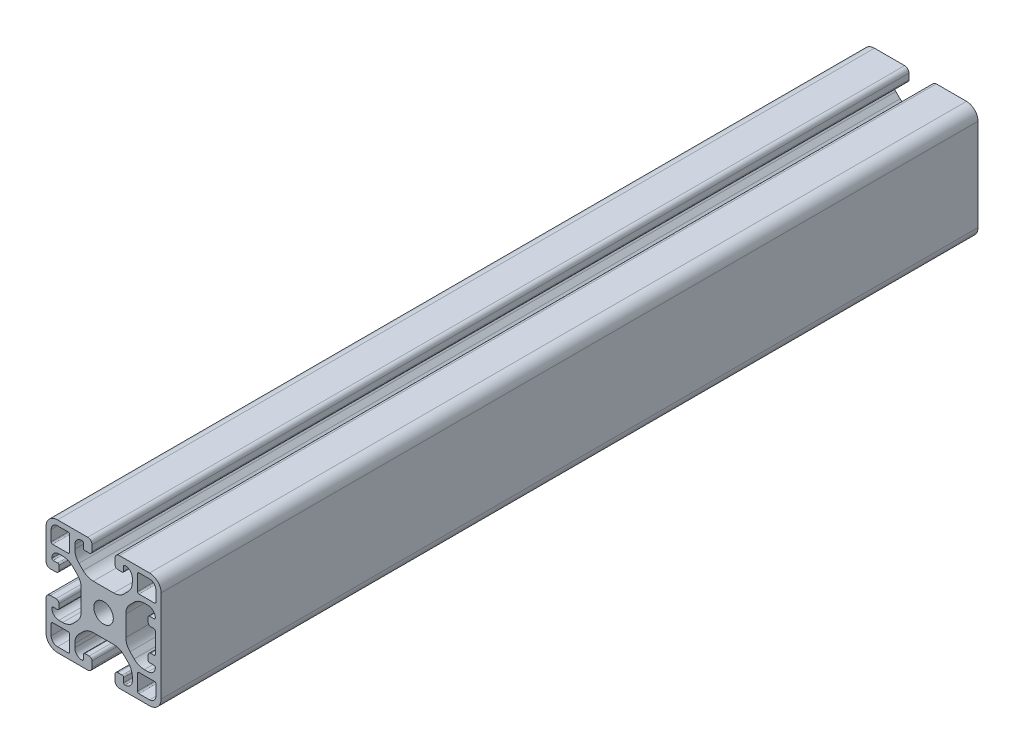
SolidWorks part; units mm, degrees
ref_plane "Piano frontale" through (0, 0, 0) normal (0, 0, 1) x (1, 0, 0)
ref_plane "Piano superiore" through (0, 0, 0) normal (0, 1, 0) x (1, 0, 0)
ref_plane "Piano destro" through (0, 0, 0) normal (1, 0, 0) x (0, 0, -1)
ref_plane "Piano1" through (0, 0, -340) normal (0, 0, -1) x (-1, 0, 0)
sketch "Schizzo1" plane through (0, 0, -340) normal (0, 0, -1) x (-1, 0, 0)
  line L0 (-12.3, -18.2) -> (-16, -18.2)
  line L1 (-18.2, -16) -> (-18.2, -12.3)
  line L2 (-17.7, -11.8) -> (-12.3, -11.8)
  line L3 (-11.8, -12.3) -> (-11.8, -17.7)
  line L4 (-11.8, 17.7) -> (-11.8, 12.3)
  line L5 (-12.3, 11.8) -> (-17.7, 11.8)
  line L6 (-18.2, 12.3) -> (-18.2, 16)
  line L7 (-16, 18.2) -> (-12.3, 18.2)
  line L8 (18.2, 16) -> (18.2, 12.3)
  line L9 (17.7, 11.8) -> (12.3, 11.8)
  line L10 (11.8, 12.3) -> (11.8, 17.7)
  line L11 (12.3, 18.2) -> (16, 18.2)
  line L12 (6.5, -15.5) -> (5, -15.5)
  line L13 (4, -16.5) -> (4, -18.5)
  line L14 (5.5, -20) -> (16, -20)
  line L15 (20, -16) -> (20, -5.5)
  line L16 (18.5, -4) -> (16.5, -4)
  line L17 (15.5, -5) -> (15.5, -6.5)
  line L18 (16, -7) -> (17.55, -7)
  line L19 (18, -7.45) -> (18, -7.5)
  line L20 (15.5, -10) -> (14.1924, -10)
  line L21 (10.6569, -8.5355) -> (9.2145, -7.0931)
  line L22 (7.75, -3.5576) -> (7.75, 3.5576)
  line L23 (9.2145, 7.0931) -> (10.6569, 8.5355)
  line L24 (14.1924, 10) -> (15.5, 10)
  line L25 (18, 7.5) -> (18, 7.45)
  line L26 (17.55, 7) -> (16, 7)
  line L27 (15.5, 6.5) -> (15.5, 5)
  line L28 (16.5, 4) -> (18.5, 4)
  line L29 (20, 5.5) -> (20, 16)
  line L30 (16, 20) -> (5.5, 20)
  line L31 (4, 18.5) -> (4, 16.5)
  line L32 (5, 15.5) -> (6.5, 15.5)
  line L33 (7, 16) -> (7, 17.55)
  line L34 (7.45, 18) -> (7.5, 18)
  line L35 (10, 15.5) -> (10, 14.1924)
  line L36 (8.5355, 10.6569) -> (7.0931, 9.2145)
  line L37 (3.5576, 7.75) -> (-3.5576, 7.75)
  line L38 (-7.0931, 9.2145) -> (-8.5355, 10.6569)
  line L39 (-10, 14.1924) -> (-10, 15.5)
  line L40 (-7.5, 18) -> (-7.45, 18)
  line L41 (-7, 17.55) -> (-7, 16)
  line L42 (-6.5, 15.5) -> (-5, 15.5)
  line L43 (-4, 16.5) -> (-4, 18.5)
  line L44 (-5.5, 20) -> (-16, 20)
  line L45 (-20, 16) -> (-20, -16)
  line L46 (-16, -20) -> (-5.5, -20)
  line L47 (-4, -18.5) -> (-4, -16.5)
  line L48 (-5, -15.5) -> (-6.5, -15.5)
  line L49 (-7, -16) -> (-7, -17.55)
  line L50 (-7.45, -18) -> (-7.5, -18)
  line L51 (-10, -15.5) -> (-10, -14.1924)
  line L52 (-8.5355, -10.6569) -> (-7.0931, -9.2145)
  line L53 (-3.5576, -7.75) -> (3.5576, -7.75)
  line L54 (7.0931, -9.2145) -> (8.5355, -10.6569)
  line L55 (10, -14.1924) -> (10, -15.5)
  line L56 (7.5, -18) -> (7.45, -18)
  line L57 (7, -17.55) -> (7, -16)
  line L58 (18.2, -12.3) -> (18.2, -16)
  line L59 (16, -18.2) -> (12.3, -18.2)
  line L60 (11.8, -17.7) -> (11.8, -12.3)
  line L61 (12.3, -11.8) -> (17.7, -11.8)
  line L62 (-16, 7) -> (-17.5, 7)
  line L63 (-15.5, 10) -> (-14.1924, 10)
  line L64 (-10.6569, 8.5355) -> (-9.2145, 7.0931)
  line L65 (-7.75, 3.5576) -> (-7.75, -3.5576)
  line L66 (-9.2145, -7.0931) -> (-10.6569, -8.5355)
  line L67 (-14.1924, -10) -> (-15.5, -10)
  line L68 (-17.5, -7) -> (-16, -7)
  line L69 (-15.5, -6.5) -> (-15.5, -5)
  line L70 (-16.5, -4) -> (-17.5, -4)
  line L71 (-18, -3.5) -> (-18, 3.5)
  line L72 (-17.5, 4) -> (-16.5, 4)
  line L73 (-15.5, 5) -> (-15.5, 6.5)
  arc A0 (-16, -18.2) -> (-18.2, -16) centre (-16, -16) cw
  arc A1 (-18.2, -12.3) -> (-17.7, -11.8) centre (-17.7, -12.3) cw
  arc A2 (-12.3, -11.8) -> (-11.8, -12.3) centre (-12.3, -12.3) cw
  arc A3 (-11.8, -17.7) -> (-12.3, -18.2) centre (-12.3, -17.7) cw
  arc A4 (-12.3, 18.2) -> (-11.8, 17.7) centre (-12.3, 17.7) cw
  arc A5 (-11.8, 12.3) -> (-12.3, 11.8) centre (-12.3, 12.3) cw
  arc A6 (-17.7, 11.8) -> (-18.2, 12.3) centre (-17.7, 12.3) cw
  arc A7 (-18.2, 16) -> (-16, 18.2) centre (-16, 16) cw
  arc A8 (16, 18.2) -> (18.2, 16) centre (16, 16) cw
  arc A9 (18.2, 12.3) -> (17.7, 11.8) centre (17.7, 12.3) cw
  arc A10 (12.3, 11.8) -> (11.8, 12.3) centre (12.3, 12.3) cw
  arc A11 (11.8, 17.7) -> (12.3, 18.2) centre (12.3, 17.7) cw
  arc A12 (5, -15.5) -> (4, -16.5) centre (5, -16.5) ccw
  arc A13 (4, -18.5) -> (5.5, -20) centre (5.5, -18.5) ccw
  arc A14 (16, -20) -> (20, -16) centre (16, -16) ccw
  arc A15 (20, -5.5) -> (18.5, -4) centre (18.5, -5.5) ccw
  arc A16 (16.5, -4) -> (15.5, -5) centre (16.5, -5) ccw
  arc A17 (15.5, -6.5) -> (16, -7) centre (16, -6.5) ccw
  arc A18 (17.55, -7) -> (18, -7.45) centre (17.55, -7.45) cw
  arc A19 (18, -7.5) -> (15.5, -10) centre (15.5, -7.5) cw
  arc A20 (14.1924, -10) -> (10.6569, -8.5355) centre (14.1924, -5) cw
  arc A21 (9.2145, -7.0931) -> (7.75, -3.5576) centre (12.75, -3.5576) cw
  arc A22 (7.75, 3.5576) -> (9.2145, 7.0931) centre (12.75, 3.5576) cw
  arc A23 (10.6569, 8.5355) -> (14.1924, 10) centre (14.1924, 5) cw
  arc A24 (15.5, 10) -> (18, 7.5) centre (15.5, 7.5) cw
  arc A25 (18, 7.45) -> (17.55, 7) centre (17.55, 7.45) cw
  arc A26 (16, 7) -> (15.5, 6.5) centre (16, 6.5) ccw
  arc A27 (15.5, 5) -> (16.5, 4) centre (16.5, 5) ccw
  arc A28 (18.5, 4) -> (20, 5.5) centre (18.5, 5.5) ccw
  arc A29 (20, 16) -> (16, 20) centre (16, 16) ccw
  arc A30 (5.5, 20) -> (4, 18.5) centre (5.5, 18.5) ccw
  arc A31 (4, 16.5) -> (5, 15.5) centre (5, 16.5) ccw
  arc A32 (6.5, 15.5) -> (7, 16) centre (6.5, 16) ccw
  arc A33 (7, 17.55) -> (7.45, 18) centre (7.45, 17.55) cw
  arc A34 (7.5, 18) -> (10, 15.5) centre (7.5, 15.5) cw
  arc A35 (10, 14.1924) -> (8.5355, 10.6569) centre (5, 14.1924) cw
  arc A36 (7.0931, 9.2145) -> (3.5576, 7.75) centre (3.5576, 12.75) cw
  arc A37 (-3.5576, 7.75) -> (-7.0931, 9.2145) centre (-3.5576, 12.75) cw
  arc A38 (-8.5355, 10.6569) -> (-10, 14.1924) centre (-5, 14.1924) cw
  arc A39 (-10, 15.5) -> (-7.5, 18) centre (-7.5, 15.5) cw
  arc A40 (-7.45, 18) -> (-7, 17.55) centre (-7.45, 17.55) cw
  arc A41 (-7, 16) -> (-6.5, 15.5) centre (-6.5, 16) ccw
  arc A42 (-5, 15.5) -> (-4, 16.5) centre (-5, 16.5) ccw
  arc A43 (-4, 18.5) -> (-5.5, 20) centre (-5.5, 18.5) ccw
  arc A44 (-16, 20) -> (-20, 16) centre (-16, 16) ccw
  arc A45 (-20, -16) -> (-16, -20) centre (-16, -16) ccw
  arc A46 (-5.5, -20) -> (-4, -18.5) centre (-5.5, -18.5) ccw
  arc A47 (-4, -16.5) -> (-5, -15.5) centre (-5, -16.5) ccw
  arc A48 (-6.5, -15.5) -> (-7, -16) centre (-6.5, -16) ccw
  arc A49 (-7, -17.55) -> (-7.45, -18) centre (-7.45, -17.55) cw
  arc A50 (-7.5, -18) -> (-10, -15.5) centre (-7.5, -15.5) cw
  arc A51 (-10, -14.1924) -> (-8.5355, -10.6569) centre (-5, -14.1924) cw
  arc A52 (-7.0931, -9.2145) -> (-3.5576, -7.75) centre (-3.5576, -12.75) cw
  arc A53 (3.5576, -7.75) -> (7.0931, -9.2145) centre (3.5576, -12.75) cw
  arc A54 (8.5355, -10.6569) -> (10, -14.1924) centre (5, -14.1924) cw
  arc A55 (10, -15.5) -> (7.5, -18) centre (7.5, -15.5) cw
  arc A56 (7.45, -18) -> (7, -17.55) centre (7.45, -17.55) cw
  arc A57 (7, -16) -> (6.5, -15.5) centre (6.5, -16) ccw
  arc A58 (17.7, -11.8) -> (18.2, -12.3) centre (17.7, -12.3) cw
  arc A59 (18.2, -16) -> (16, -18.2) centre (16, -16) cw
  arc A60 (12.3, -18.2) -> (11.8, -17.7) centre (12.3, -17.7) cw
  arc A61 (11.8, -12.3) -> (12.3, -11.8) centre (12.3, -12.3) cw
  circle A62 centre (0, 0) radius 3.4
  arc A63 (-15.5, 6.5) -> (-16, 7) centre (-16, 6.5) ccw
  arc A64 (-17.5, 7) -> (-18, 7.5) centre (-17.5, 7.5) cw
  arc A65 (-18, 7.5) -> (-15.5, 10) centre (-15.5, 7.5) cw
  arc A66 (-14.1924, 10) -> (-10.6569, 8.5355) centre (-14.1924, 5) cw
  arc A67 (-9.2145, 7.0931) -> (-7.75, 3.5576) centre (-12.75, 3.5576) cw
  arc A68 (-7.75, -3.5576) -> (-9.2145, -7.0931) centre (-12.75, -3.5576) cw
  arc A69 (-10.6569, -8.5355) -> (-14.1924, -10) centre (-14.1924, -5) cw
  arc A70 (-15.5, -10) -> (-18, -7.5) centre (-15.5, -7.5) cw
  arc A71 (-18, -7.5) -> (-17.5, -7) centre (-17.5, -7.5) cw
  arc A72 (-16, -7) -> (-15.5, -6.5) centre (-16, -6.5) ccw
  arc A73 (-15.5, -5) -> (-16.5, -4) centre (-16.5, -5) ccw
  arc A74 (-17.5, -4) -> (-18, -3.5) centre (-17.5, -3.5) cw
  arc A75 (-18, 3.5) -> (-17.5, 4) centre (-17.5, 3.5) cw
  arc A76 (-16.5, 4) -> (-15.5, 5) centre (-16.5, 5) ccw
extrude "Estrusione-Estrusione1" add sketch "Schizzo1" against normal blind 284
